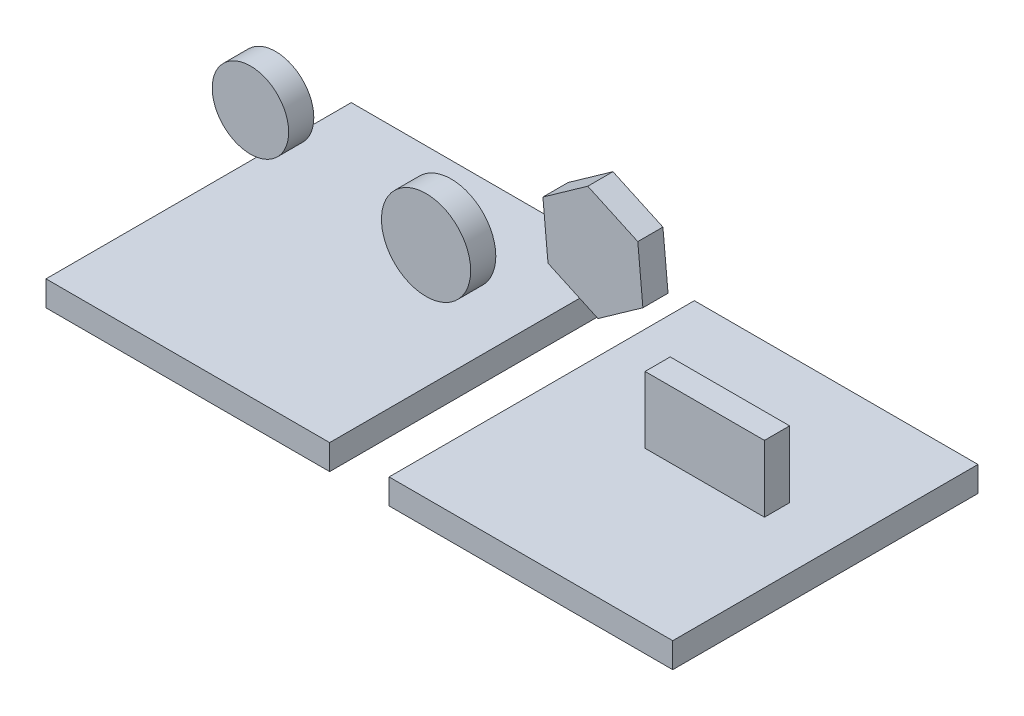
SolidWorks part; units mm, degrees
material "AISI 1020"
ref_plane "Front Plane" through (0, 0, 0) normal (0, 0, 1) x (1, 0, 0)
ref_plane "Top Plane" through (0, 0, 0) normal (0, 1, 0) x (1, 0, 0)
ref_plane "Right Plane" through (0, 0, 0) normal (1, 0, 0) x (0, 0, -1)
sketch "Sketch1" plane through (0, 0, 0) normal (0, 1, 0) x (1, 0, 0)
  line L1 (-124.6102, -60.6916) -> (124.6102, -60.6916)
  line L2 (-124.6102, -60.6916) -> (-124.6102, 60.6916)
  line L3 (-124.6102, 60.6916) -> (124.6102, 60.6916)
  line L4 (124.6102, -60.6916) -> (124.6102, 60.6916)
  line L5 (-124.6102, -60.6916) -> (124.6102, 60.6916) construction
  line L6 (-124.6102, 60.6916) -> (124.6102, -60.6916) construction
  point P0 (0, 0)
extrude "Boss-Extrude1" add sketch "Sketch1" along normal blind 10
sketch "Sketch2" plane through (0, 10, 0) normal (0, 1, 0) x (1, 0, 0)
  line L1 (-11.8179, -79.3975) -> (11.8179, -79.3975)
  line L2 (-11.8179, -79.3975) -> (-11.8179, 79.3975)
  line L3 (-11.8179, 79.3975) -> (11.8179, 79.3975)
  line L4 (11.8179, -79.3975) -> (11.8179, 79.3975)
  line L5 (-11.8179, -79.3975) -> (11.8179, 79.3975) construction
  line L6 (-11.8179, 79.3975) -> (11.8179, -79.3975) construction
  point P0 (0, 0)
extrude "Cut-Extrude1" cut sketch "Sketch2" against normal through all
sketch "Sketch3" plane through (0, 0, 0) normal (0, 0, 1) x (1, 0, 0)
  line L1 (62.0441, 68.0136) -> (60.0149, 89.7924)
  line L2 (60.0149, 89.7924) -> (40.1393, 98.9244)
  line L3 (40.1393, 98.9244) -> (22.2929, 86.2777)
  line L4 (22.2929, 86.2777) -> (24.3221, 64.4989)
  line L5 (24.3221, 64.4989) -> (44.1977, 55.3668)
  line L6 (44.1977, 55.3668) -> (62.0441, 68.0136)
  line L7 (62.9094, 20.0565) -> (110.3902, 20.0565)
  line L8 (62.9094, 20.0565) -> (62.9094, 46.5265)
  line L9 (62.9094, 46.5265) -> (110.3902, 46.5265)
  line L10 (110.3902, 20.0565) -> (110.3902, 46.5265)
  line L11 (62.9094, 20.0565) -> (110.3902, 46.5265) construction
  line L12 (62.9094, 46.5265) -> (110.3902, 20.0565) construction
  circle A0 centre (-94.0062, 58.0758) radius 15.1984
  circle A1 centre (-24.173, 46.5265) radius 17.735
  circle A2 centre (42.1685, 77.1456) radius 18.9427 construction
  point P5 (86.6498, 33.2915)
extrude "Boss-Extrude2" add sketch "Sketch3" along normal blind 10 separate body
